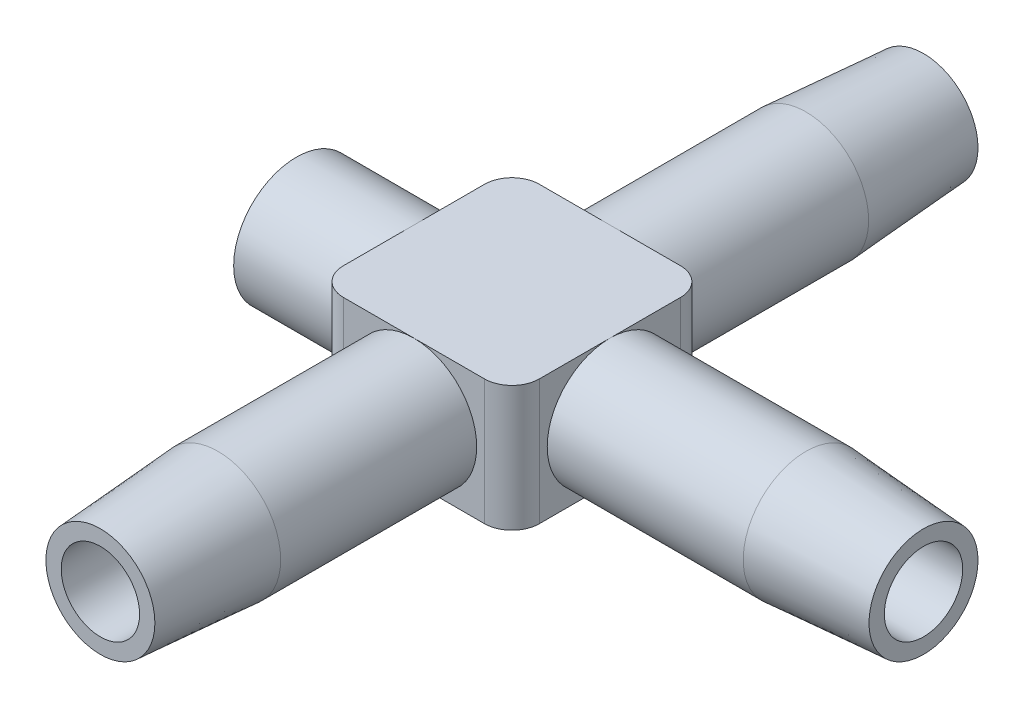
SolidWorks part; units mm, degrees
ref_plane "Front Plane" through (0, 0, 0) normal (0, 0, 1) x (1, 0, 0)
ref_plane "Top Plane" through (0, 0, 0) normal (0, 1, 0) x (1, 0, 0)
ref_plane "Right Plane" through (0, 0, 0) normal (1, 0, 0) x (0, 0, -1)
sketch "Sketch1" plane through (0, 0, 0) normal (0, 1, 0) x (1, 0, 0)
  line L1 (-5, 5) -> (5, 5)
  line L2 (-5, 5) -> (-5, -5)
  line L3 (-5, -5) -> (5, -5)
  line L4 (5, 5) -> (5, -5)
  point P4 (0, 5)
  point P6 (5, 0)
  dimension "D1" = 10
  dimension "D2" = 10
extrude "Boss-Extrude1" add sketch "Sketch1" along normal blind 6.4
sketch "Sketch2" plane through (0, 0, 5) normal (0, 0, 1) x (1, 0, 0)
  line L0 (-5, 6.4) -> (-5, 0) construction
  circle A0 centre (0, 3.2) radius 3.2
  point P8 (-5, 3.2)
  dimension "D1" = 6.4
extrude "Boss-Extrude2" add sketch "Sketch2" along normal blind 10
sketch "Sketch4" plane through (5, 0, 0) normal (1, 0, 0) x (0, 0, -1)
  line L0 (-5, 6.4) -> (-5, 0) construction
  circle A0 centre (0, 3.2) radius 3.2
  point P7 (-5, 3.2)
  dimension "D1" = 6.4
extrude "Boss-Extrude3" add sketch "Sketch4" along normal blind 10
sketch "Sketch8" plane through (15, 0, 0) normal (1, 0, 0) x (0, 0, -1)
  circle A2 centre (0, 3.2) radius 3.2
  dimension "D1" = 6.4
extrude "Boss-Extrude4" add sketch "Sketch8" along normal blind 6 draft 4
sketch "Sketch10" plane through (0, 0, 15) normal (0, 0, 1) x (1, 0, 0)
  circle A0 centre (0, 3.2) radius 3.2
  dimension "D1" = 6.4
extrude "Boss-Extrude5" add sketch "Sketch10" along normal blind 6 draft 4
mirror "Mirror2" about plane through (0, 0, 0) normal (0, 0, 1) of "Boss-Extrude5", "Boss-Extrude2"
fillet "Fillet1" radius 1.4 4 edges at (-5, 3.2, 5) (-5, 3.2, -5) (5, 3.2, -5) (5, 3.2, 5)
sketch "Sketch11" plane through (0, 0, 21) normal (0, 0, 1) x (1, 0, 0)
  circle A0 centre (0, 3.2) radius 2
  dimension "D1" = 4
extrude "Cut-Extrude5" cut sketch "Sketch11" against normal through all
sketch "Sketch9" plane through (21, 0, 0) normal (1, 0, 0) x (0, 0, -1)
  circle A0 centre (0, 3.2) radius 2
  dimension "D1" = 4
extrude "Cut-Extrude6" cut sketch "Sketch9" against normal up to next
sketch "Sketch12" plane through (-5, 0, 0) normal (-1, 0, 0) x (0, 0, 1)
  line L0 (-3.6, 6.4) -> (-3.6, 0) construction
  circle A0 centre (0, 3.2) radius 3.2
  circle A1 centre (0, 3.2) radius 1.8
  point P3 (0, 0)
  point P6 (-3.6, 3.2)
  point P7 (0, 0)
  dimension "D1" = 6.4
  dimension "D2" = 1.4
extrude "Boss-Extrude6" add sketch "Sketch12" along normal blind 6
